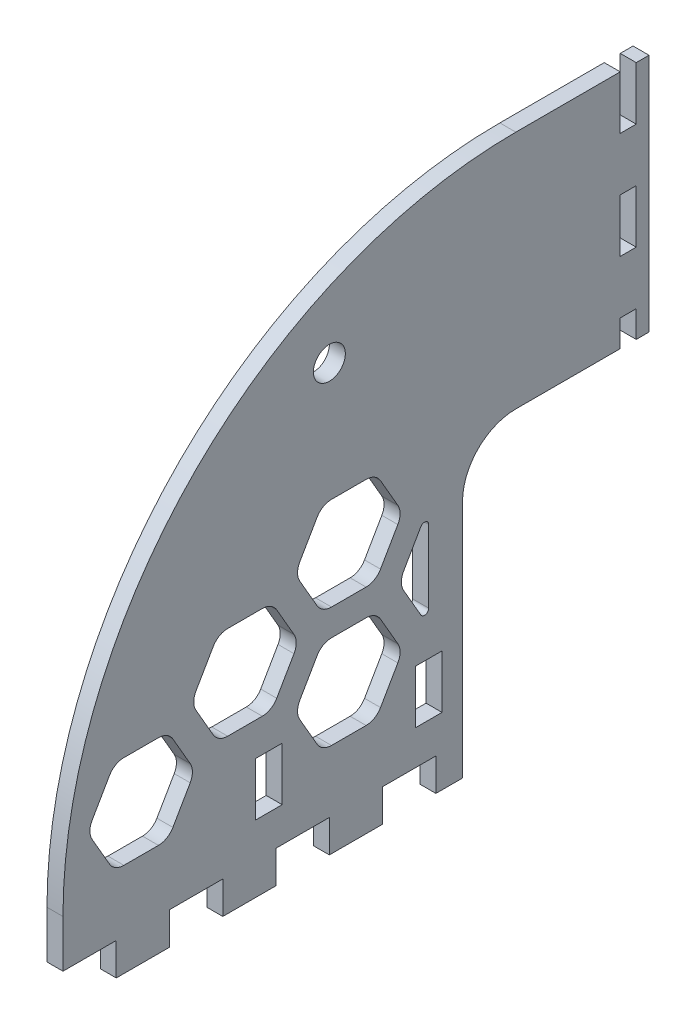
SolidWorks part; units mm, degrees
material "Pine"
ref_plane "Front Plane" through (0, 0, 0) normal (0, 0, 1) x (1, 0, 0)
ref_plane "Top Plane" through (0, 0, 0) normal (0, 1, 0) x (1, 0, 0)
ref_plane "Right Plane" through (0, 0, 0) normal (1, 0, 0) x (0, 0, -1)
sketch "Sketch1" plane through (0, 0, 0) normal (1, 0, 0) x (0, 0, -1)
  line L1 (0, 0) -> (110, 0)
  line L2 (0, 0) -> (0, 15)
  line L3 (85, 100) -> (110, 100)
  line L4 (110, 0) -> (110, 100)
  arc A0 (0, 15) -> (85, 100) centre (85, 15) cw
  circle A1 centre (50, 80) radius 3
  point P7 (0, 100)
  dimension "D3" = 85
  dimension "D4" = 80
  dimension "D6" = 6
  dimension "D1" = 100
  dimension "D2" = 110
  dimension "D5" = 50
extrude "Boss-Extrude1" add sketch "Sketch1" along normal blind 3
sketch "Sketch2" plane through (3, 0, 0) normal (1, 0, 0) x (0, 0, -1)
  line L1 (110, 0) -> (75, 0)
  line L2 (110, 0) -> (110, 55)
  line L3 (110, 55) -> (85, 55)
  line L4 (75, 0) -> (75, 45)
  arc A0 (85, 55) -> (75, 45) centre (85, 45) ccw
  point P7 (75, 55)
  dimension "D3" = 10
  dimension "D1" = 55
  dimension "D2" = 35
extrude "Cut-Extrude1" cut sketch "Sketch2" against normal through all both and the other way through all
sketch "Sketch4" plane through (3, 0, 0) normal (1, 0, 0) x (0, 0, -1)
  line L0 (20, 0) -> (30, 0)
  line L1 (0, 0) -> (10, 0)
  line L2 (0, 0) -> (0, 6.1)
  line L3 (0, 6.1) -> (10, 6.1)
  line L4 (10, 0) -> (10, 6.1)
  line L5 (20, 0) -> (20, 6.1)
  line L6 (20, 6.1) -> (30, 6.1)
  line L7 (30, 0) -> (30, 6.1)
  line L8 (40, 0) -> (50, 0)
  line L9 (40, 0) -> (40, 6.1)
  line L10 (40, 6.1) -> (50, 6.1)
  line L11 (50, 0) -> (50, 6.1)
  line L12 (60, 0) -> (70, 0)
  line L13 (60, 0) -> (60, 6.1)
  line L14 (60, 6.1) -> (70, 6.1)
  line L15 (70, 0) -> (70, 6.1)
  line L16 (0, 0) -> (20, 0) construction
  dimension "D1" = 6.1
  dimension "D2" = 10
  dimension "D4" = 20
  dimension "D3" = 4
extrude "Cut-Extrude2" cut sketch "Sketch4" against normal through all both and the other way through all
sketch "Sketch5" plane through (0, 0, 0) normal (-1, 0, 0) x (0, 0, 1)
  line L1 (-71.15, 22.6) -> (-66.15, 22.6)
  line L2 (-71.15, 22.6) -> (-71.15, 12.6)
  line L3 (-71.15, 12.6) -> (-66.15, 12.6)
  line L4 (-66.15, 22.6) -> (-66.15, 12.6)
  line L5 (-66.15, 12.6) -> (-71.15, 12.6) construction
  line L7 (-41.15, 22.6) -> (-36.15, 22.6)
  line L8 (-41.15, 22.6) -> (-41.15, 12.6)
  line L9 (-41.15, 12.6) -> (-36.15, 12.6)
  line L10 (-36.15, 22.6) -> (-36.15, 12.6)
  point P13 (-66.15, 16.1)
extrude "Cut-Extrude3" cut sketch "Sketch5" against normal through all both and the other way through all
sketch "Sketch6" plane through (3, 0, 0) normal (1, 0, 0) x (0, 0, -1)
  line L0 (110, 100) -> (85, 100) construction
  line L1 (104.6, 90) -> (107.6, 90)
  line L2 (104.6, 90) -> (104.6, 100)
  line L3 (104.6, 100) -> (107.6, 100)
  line L4 (107.6, 90) -> (107.6, 100)
  line L5 (107.6, 90) -> (107.6, 100) construction
  line L7 (104.6, 80) -> (107.6, 80)
  line L8 (104.6, 80) -> (104.6, 70)
  line L9 (104.6, 70) -> (107.6, 70)
  line L10 (107.6, 80) -> (107.6, 70)
  line L11 (104.6, 60) -> (107.6, 60)
  line L12 (104.6, 60) -> (104.6, 45)
  line L13 (104.6, 45) -> (107.6, 45)
  line L14 (107.6, 60) -> (107.6, 45)
extrude "Cut-Extrude4" cut sketch "Sketch6" against normal through all
sketch "Sketch7" plane through (3, 0, 0) normal (1, 0, 0) x (0, 0, -1)
  line L1 (62.8515, 50.4125) -> (59.6039, 56.0375)
  line L2 (56.8976, 57.6) -> (50.4024, 57.6)
  line L3 (47.6961, 56.0375) -> (44.4485, 50.4125)
  line L4 (44.4485, 47.2875) -> (47.6961, 41.6625)
  line L5 (50.4024, 40.1) -> (56.8976, 40.1)
  line L6 (59.6039, 41.6625) -> (62.8515, 47.2875)
  line L8 (67.1816, 44.7875) -> (63.9341, 39.1625)
  line L9 (63.9341, 36.0375) -> (67.1816, 30.4125)
  line L12 (68.6395, 44.3969) -> (68.6395, 30.8031)
  line L13 (62.8515, 27.9125) -> (59.6039, 33.5375)
  line L14 (56.8976, 35.1) -> (50.4024, 35.1)
  line L15 (47.6961, 33.5375) -> (44.4485, 27.9125)
  line L16 (44.4485, 24.7875) -> (47.6961, 19.1625)
  line L17 (50.4024, 17.6) -> (56.8976, 17.6)
  line L18 (59.6039, 19.1625) -> (62.8515, 24.7875)
  line L19 (41.15, 17.6) -> (66.15, 17.6) construction
  line L20 (41.15, 22.6) -> (41.15, 12.6) construction
  line L21 (66.15, 12.6) -> (66.15, 22.6) construction
  line L22 (53.65, 17.6) -> (53.65, 26.35) construction
  line L23 (43.3659, 39.1625) -> (40.1184, 44.7875)
  line L24 (37.412, 46.35) -> (30.9168, 46.35)
  line L25 (28.2105, 44.7875) -> (24.9629, 39.1625)
  line L26 (24.9629, 36.0375) -> (28.2105, 30.4125)
  line L27 (30.9168, 28.85) -> (37.412, 28.85)
  line L28 (40.1184, 30.4125) -> (43.3659, 36.0375)
  line L29 (23.8804, 27.9125) -> (20.6328, 33.5375)
  line L30 (17.9265, 35.1) -> (11.4313, 35.1)
  line L31 (8.7249, 33.5375) -> (5.4773, 27.9125)
  line L32 (5.4773, 24.7875) -> (8.7249, 19.1625)
  line L33 (11.4313, 17.6) -> (17.9265, 17.6)
  line L34 (20.6328, 19.1625) -> (23.8804, 24.7875)
  circle A0 centre (53.65, 48.85) radius 8.75 construction
  arc A1 (56.8976, 40.1) -> (59.6039, 41.6625) centre (56.8976, 43.225) ccw
  arc A2 (47.6961, 41.6625) -> (50.4024, 40.1) centre (50.4024, 43.225) ccw
  arc A3 (44.4485, 50.4125) -> (44.4485, 47.2875) centre (47.1548, 48.85) ccw
  arc A4 (50.4024, 57.6) -> (47.6961, 56.0375) centre (50.4024, 54.475) ccw
  arc A5 (59.6039, 56.0375) -> (56.8976, 57.6) centre (56.8976, 54.475) ccw
  arc A6 (62.8515, 50.4125) -> (62.8515, 47.2875) centre (60.1452, 48.85) cw
  arc A7 (68.6395, 45.1065) -> (68.6395, 30.0935) centre (73.1356, 37.6) ccw construction
  arc A10 (63.9341, 39.1625) -> (63.9341, 36.0375) centre (66.6404, 37.6) ccw
  arc A12 (68.6395, 44.3969) -> (67.1816, 44.7875) centre (67.8582, 44.3969) ccw
  arc A13 (67.1816, 30.4125) -> (68.6395, 30.8031) centre (67.8582, 30.8031) ccw
  arc A14 (56.8976, 17.6) -> (59.6039, 19.1625) centre (56.8976, 20.725) ccw
  arc A15 (47.6961, 19.1625) -> (50.4024, 17.6) centre (50.4024, 20.725) ccw
  arc A16 (44.4485, 27.9125) -> (44.4485, 24.7875) centre (47.1548, 26.35) ccw
  arc A17 (50.4024, 35.1) -> (47.6961, 33.5375) centre (50.4024, 31.975) ccw
  arc A18 (59.6039, 33.5375) -> (56.8976, 35.1) centre (56.8976, 31.975) ccw
  arc A19 (62.8515, 27.9125) -> (62.8515, 24.7875) centre (60.1452, 26.35) cw
  circle A20 centre (53.65, 26.35) radius 8.75 construction
  circle A21 centre (34.1644, 37.6) radius 8.75 construction
  arc A22 (37.412, 28.85) -> (40.1184, 30.4125) centre (37.412, 31.975) ccw
  arc A23 (28.2105, 30.4125) -> (30.9168, 28.85) centre (30.9168, 31.975) ccw
  arc A24 (24.9629, 39.1625) -> (24.9629, 36.0375) centre (27.6692, 37.6) ccw
  arc A25 (30.9168, 46.35) -> (28.2105, 44.7875) centre (30.9168, 43.225) ccw
  arc A26 (40.1184, 44.7875) -> (37.412, 46.35) centre (37.412, 43.225) ccw
  arc A27 (43.3659, 39.1625) -> (43.3659, 36.0375) centre (40.6596, 37.6) cw
  arc A28 (17.9265, 17.6) -> (20.6328, 19.1625) centre (17.9265, 20.725) ccw
  arc A29 (8.7249, 19.1625) -> (11.4313, 17.6) centre (11.4313, 20.725) ccw
  arc A30 (5.4773, 27.9125) -> (5.4773, 24.7875) centre (8.1837, 26.35) ccw
  arc A31 (11.4313, 35.1) -> (8.7249, 33.5375) centre (11.4313, 31.975) ccw
  arc A32 (20.6328, 33.5375) -> (17.9265, 35.1) centre (17.9265, 31.975) ccw
  arc A33 (23.8804, 27.9125) -> (23.8804, 24.7875) centre (21.174, 26.35) cw
  circle A34 centre (14.6789, 26.35) radius 8.75 construction
  dimension "D1" = 17.5
  dimension "D2" = 3.125
  dimension "D3" = 17.5
  dimension "D4" = 0.7812
  dimension "D9" = 17.5
  dimension "D10" = 2
  dimension "D5" = 5
  dimension "D7" = 5
  dimension "D8" = 5
  dimension "D11" = 5
  dimension "D12" = 5
  dimension "D6" = 2
extrude "Cut-Extrude5" cut sketch "Sketch7" against normal through all
